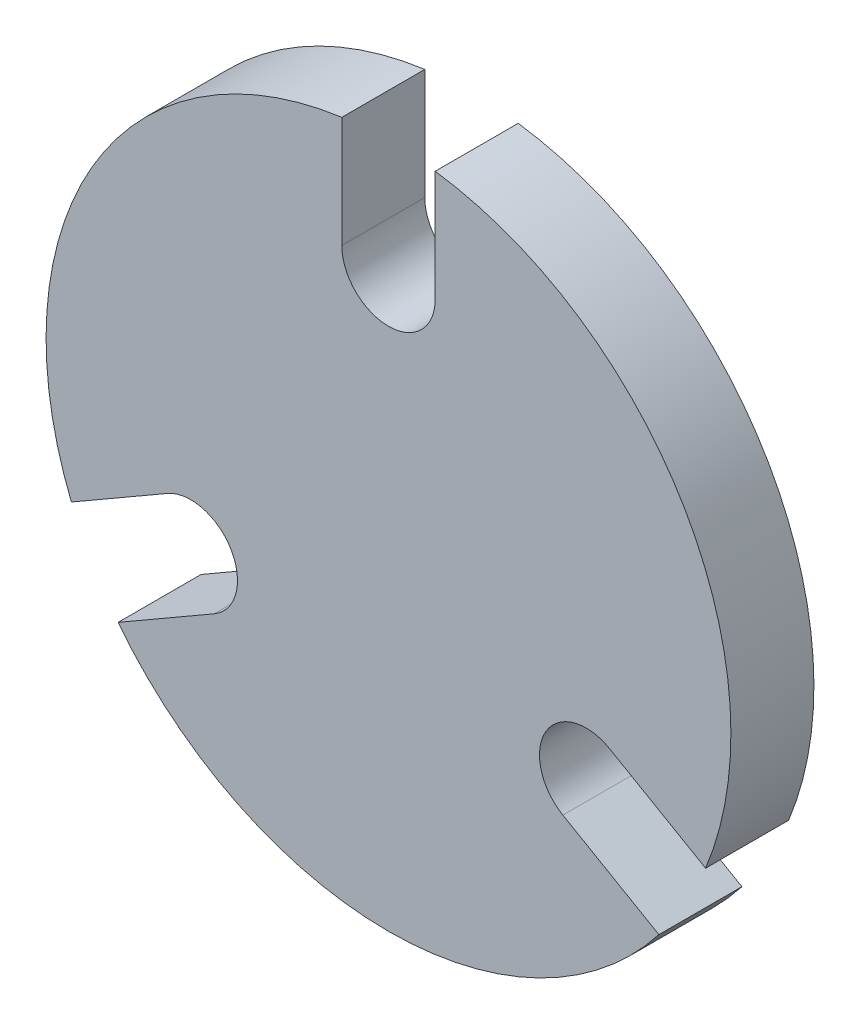
SolidWorks part; units mm, degrees
ref_plane "Front Plane" through (0, 0, 0) normal (0, 0, 1) x (1, 0, 0)
ref_plane "Top Plane" through (0, 0, 0) normal (0, 1, 0) x (1, 0, 0)
ref_plane "Right Plane" through (0, 0, 0) normal (1, 0, 0) x (0, 0, -1)
sketch "Sketch2" plane through (0, 0, 0) normal (0, 0, 1) x (1, 0, 0)
  line L0 (-0.45, 2.2) -> (-0.45, 3.2692)
  line L1 (0.45, 2.2) -> (0.45, 3.2692)
  line L2 (2.1303, -0.7103) -> (3.0562, -1.2449)
  line L3 (1.6803, -1.4897) -> (2.6062, -2.0243)
  line L4 (-1.6803, -1.4897) -> (-2.6062, -2.0243)
  line L5 (-2.1303, -0.7103) -> (-3.0562, -1.2449)
  arc A1 (-0.45, 3.2692) -> (-3.0562, -1.2449) centre (0, 0) ccw
  arc A2 (-0.45, 2.2) -> (0.45, 2.2) centre (0, 2.2) ccw
  arc A3 (2.1303, -0.7103) -> (1.6803, -1.4897) centre (1.9053, -1.1) ccw
  arc A4 (-1.6803, -1.4897) -> (-2.1303, -0.7103) centre (-1.9053, -1.1) ccw
  arc A5 (0.45, 3.2692) -> (-0.45, 3.2692) centre (0, 0) ccw construction
  arc A6 (3.0562, -1.2449) -> (0.45, 3.2692) centre (0, 0) ccw
  arc A7 (2.6062, -2.0243) -> (3.0562, -1.2449) centre (0, 0) ccw construction
  arc A8 (-2.6062, -2.0243) -> (2.6062, -2.0243) centre (0, 0) ccw
  arc A9 (-3.0562, -1.2449) -> (-2.6062, -2.0243) centre (0, 0) ccw construction
  point P9 (2.741, -1.3224)
  point P10 (0, 0)
  point P20 (0, 0)
  dimension "D1" = 0.9
  dimension "D2" = 6.6
  dimension "D3" = 2.2
  dimension "D4" = 3
extrude "Boss-Extrude1" add sketch "Sketch2" along normal blind 0.8
